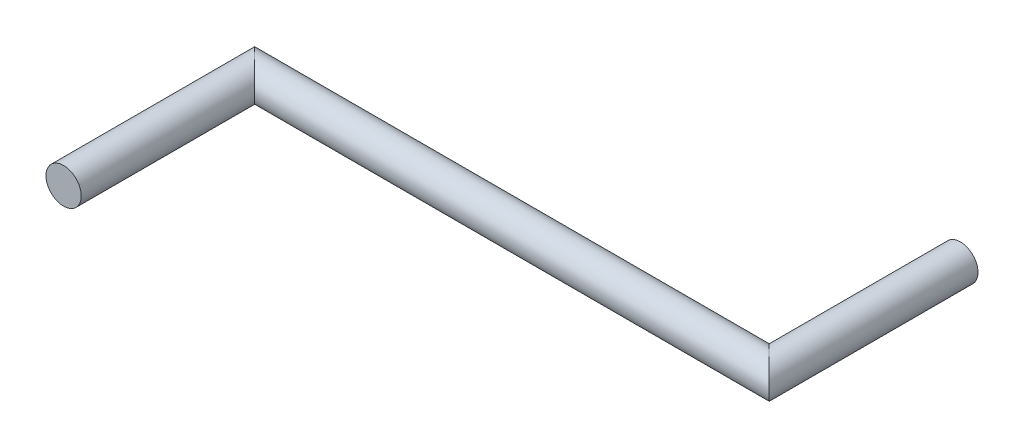
SolidWorks part; units mm, degrees
material "Cast Stainless Steel"
ref_plane "Front Plane" through (0, 0, 0) normal (0, 0, 1) x (1, 0, 0)
ref_plane "Top Plane" through (0, 0, 0) normal (0, 1, 0) x (1, 0, 0)
ref_plane "Right Plane" through (0, 0, 0) normal (1, 0, 0) x (0, 0, -1)
sketch "Sketch1" plane through (0, 0, 0) normal (0, 1, 0) x (1, 0, 0)
  line L0 (-8.75, 0) -> (8.75, 0)
  line L1 (8.75, 0) -> (8.75, 6.5)
  line L2 (-8.75, 0) -> (-8.75, -6.5)
  point P4 (0, 0)
  dimension "D1" = 6.5
  dimension "D2" = 6.5
  dimension "D3" = 17.5
ref_plane "Plane1" through (-8.75, 0, 6.5) normal (0, 0, 1) x (1, 0, 0)
sketch "Sketch2" plane through (-8.75, 0, 6.5) normal (0, 0, 1) x (1, 0, 0)
  circle A0 centre (0, 0) radius 0.6
  dimension "D1" = 1.2
sweep "Sweep1" add profiles "Sketch2" path "Sketch1"
